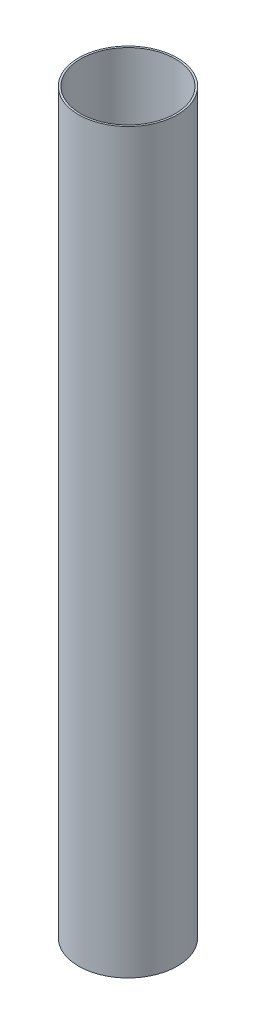
SolidWorks part; units mm, degrees
ref_plane "Front Plane" through (0, 0, 0) normal (0, 0, 1) x (1, 0, 0)
ref_plane "Top Plane" through (0, 0, 0) normal (0, 1, 0) x (1, 0, 0)
ref_plane "Right Plane" through (0, 0, 0) normal (1, 0, 0) x (0, 0, -1)
sketch "Sketch1" plane through (0, 0, 0) normal (0, 1, 0) x (1, 0, 0)
  circle A0 centre (0, 0) radius 39.624
  circle A1 centre (0, 0) radius 38.1
  dimension "D1" = 79.248
  dimension "D2" = 76.2
extrude "Boss-Extrude1" add sketch "Sketch1" along normal blind 592.36
